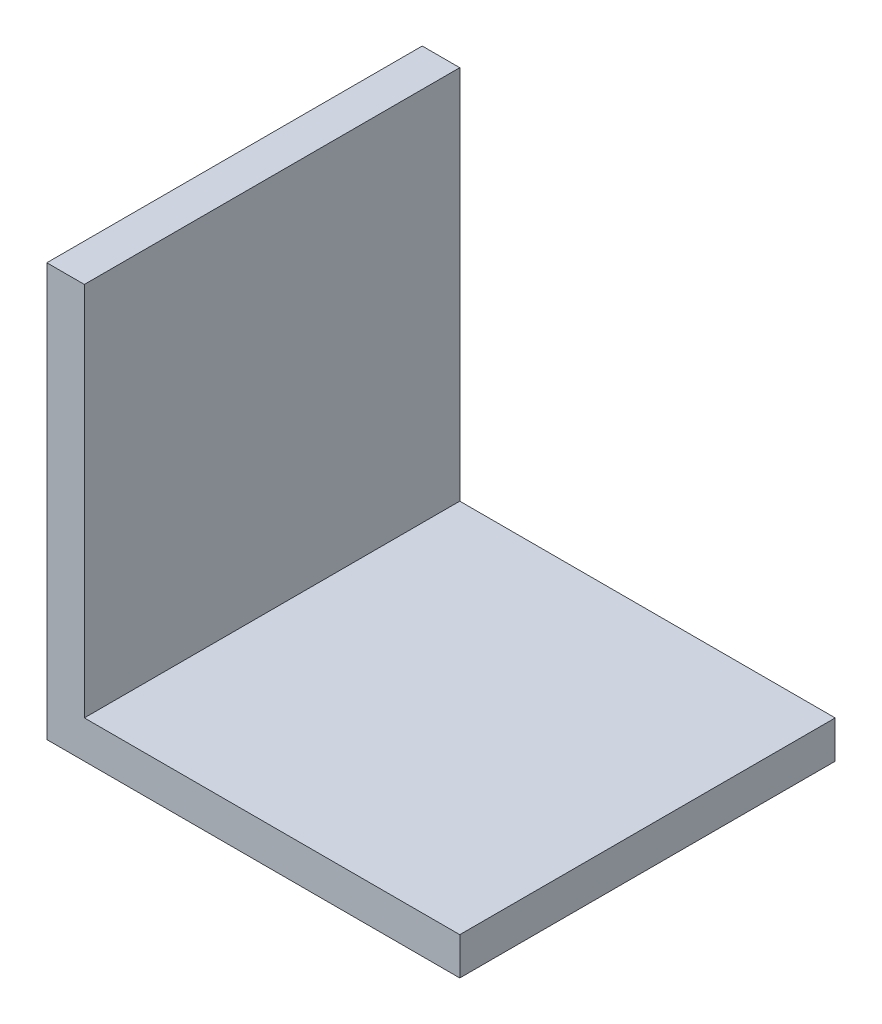
SolidWorks part; units mm, degrees
ref_plane "Спереди" through (0, 0, 0) normal (0, 0, 1) x (1, 0, 0)
ref_plane "Сверху" through (0, 0, 0) normal (0, 1, 0) x (1, 0, 0)
ref_plane "Справа" through (0, 0, 0) normal (1, 0, 0) x (0, 0, -1)
sketch "Эскиз1" plane through (0, 0, 0) normal (0, 0, 1) x (1, 0, 0)
  line L0 (0, 30) -> (0, 0)
  line L1 (0, 0) -> (30, 0)
extrude "Вытянуть-Тонкостенный1" add sketch "Эскиз1" against normal blind 30 thin
